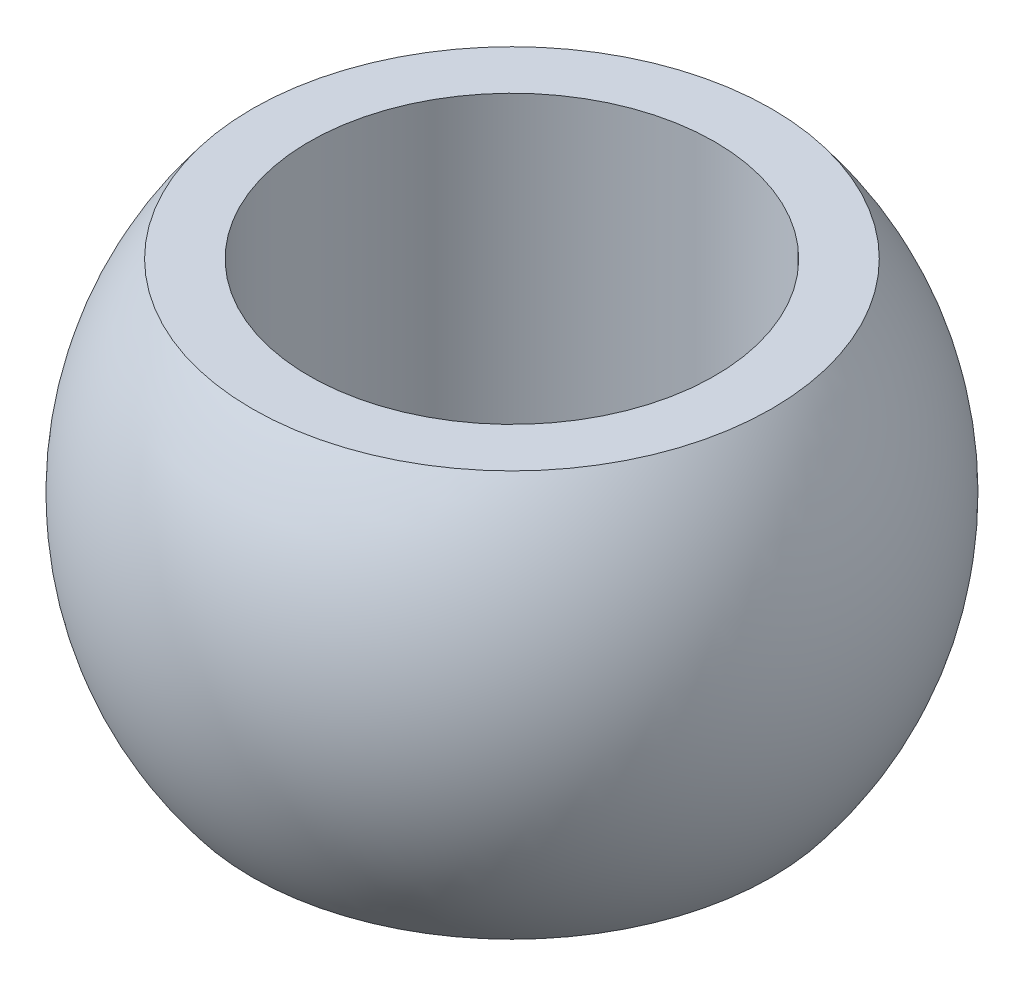
SolidWorks part; units mm, degrees
ref_plane "Front Plane" through (0, 0, 0) normal (0, 0, 1) x (1, 0, 0)
ref_plane "Top Plane" through (0, 0, 0) normal (0, 1, 0) x (1, 0, 0)
ref_plane "Right Plane" through (0, 0, 0) normal (1, 0, 0) x (0, 0, -1)
sketch "Sketch1" plane through (0, 0, 0) normal (0, 0, 1) x (1, 0, 0)
  line L0 (0, -18.2177) -> (0, 30.6268) construction
  line L1 (-4, 4) -> (-4, -4)
  line L2 (-5.1235, 4) -> (-4, 4)
  line L3 (-5.1235, -4) -> (-4, -4)
  arc A0 (-5.1235, 4) -> (-5.1235, -4) centre (0, 0) ccw
  dimension "D2" = 6.5
  dimension "D3" = 4
  dimension "D1" = 4
  dimension "D4" = 4
revolve "Revolve1" add sketch "Sketch1" angle 360 about L0
